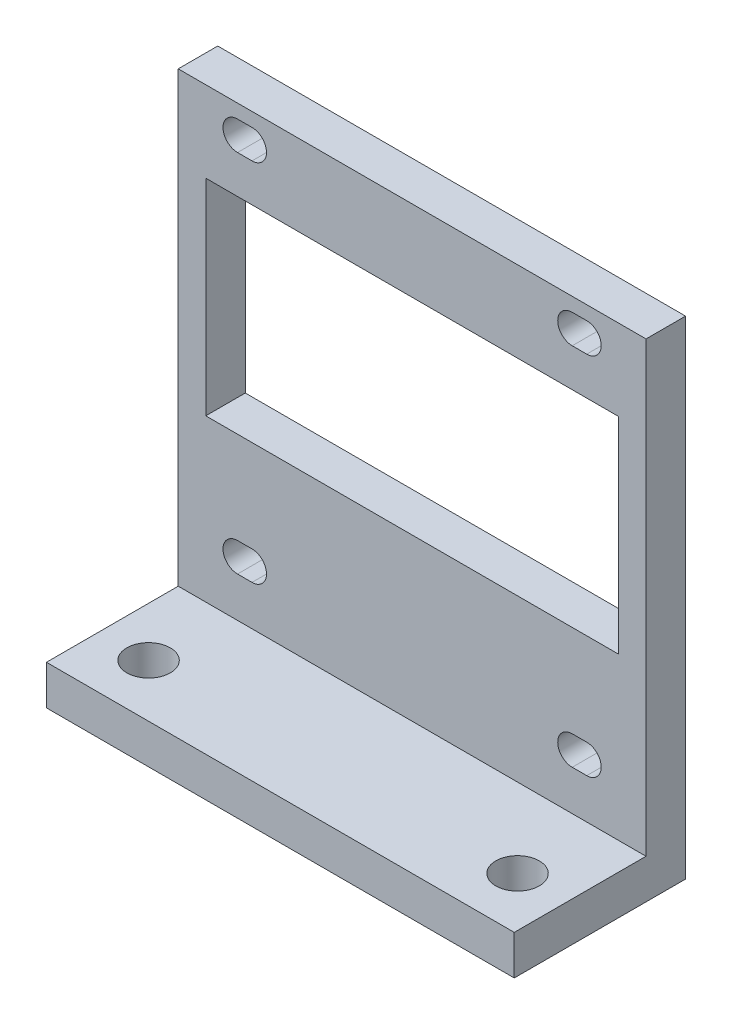
SolidWorks part; units mm, degrees
ref_plane "Front Plane" through (0, 0, 0) normal (0, 0, 1) x (1, 0, 0)
ref_plane "Top Plane" through (0, 0, 0) normal (0, 1, 0) x (1, 0, 0)
ref_plane "Right Plane" through (0, 0, 0) normal (1, 0, 0) x (0, 0, -1)
sketch "Sketch1" plane through (0, 0, 0) normal (0, 0, 1) x (1, 0, 0)
  line L0 (4.5, 34.85) -> (5.6, 34.85) construction
  line L5 (0, 5) -> (35.5, 5) construction
  line L6 (0, 5) -> (0, 37) construction
  line L7 (0, 37) -> (35.5, 37) construction
  line L8 (35.5, 5) -> (35.5, 37) construction
  line L9 (4.5, 35.95) -> (5.6, 35.95)
  line L10 (4.5, 33.75) -> (5.6, 33.75)
  line L11 (29.9, 34.85) -> (31, 34.85) construction
  line L12 (29.9, 35.95) -> (31, 35.95)
  line L13 (29.9, 33.75) -> (31, 33.75)
  line L14 (29.9, 7.15) -> (31, 7.15) construction
  line L15 (29.9, 8.25) -> (31, 8.25)
  line L16 (29.9, 6.05) -> (31, 6.05)
  line L17 (4.5, 7.15) -> (5.6, 7.15) construction
  line L18 (4.5, 8.25) -> (5.6, 8.25)
  line L19 (4.5, 6.05) -> (5.6, 6.05)
  line L21 (0, 0) -> (35.5, 0)
  line L22 (0, 0) -> (0, 37)
  line L23 (0, 37) -> (35.5, 37)
  line L24 (35.5, 0) -> (35.5, 37)
  line L25 (2.09, 15.24) -> (33.41, 15.24)
  line L26 (2.09, 15.24) -> (2.09, 30.86)
  line L27 (2.09, 30.86) -> (33.41, 30.86)
  line L28 (33.41, 15.24) -> (33.41, 30.86)
  arc A0 (4.5, 35.95) -> (4.5, 33.75) centre (4.5, 34.85) ccw
  arc A1 (5.6, 33.75) -> (5.6, 35.95) centre (5.6, 34.85) ccw
  arc A2 (29.9, 35.95) -> (29.9, 33.75) centre (29.9, 34.85) ccw
  arc A3 (31, 33.75) -> (31, 35.95) centre (31, 34.85) ccw
  arc A4 (29.9, 8.25) -> (29.9, 6.05) centre (29.9, 7.15) ccw
  arc A5 (31, 6.05) -> (31, 8.25) centre (31, 7.15) ccw
  arc A6 (4.5, 8.25) -> (4.5, 6.05) centre (4.5, 7.15) ccw
  arc A7 (5.6, 6.05) -> (5.6, 8.25) centre (5.6, 7.15) ccw
  point P7 (5.05, 34.85)
  point P16 (30.45, 34.85)
  point P23 (30.45, 7.15)
  point P30 (5.05, 7.15)
  dimension "D1" = 3.3
  dimension "D2" = 1.1
  dimension "D3" = 5.05
  dimension "D4" = 2.15
  dimension "D5" = 35.5
  dimension "D6" = 32
  dimension "D9" = 5
  dimension "D10" = 15.62
  dimension "D11" = 31.32
  dimension "D12" = 6.14
  dimension "D13" = 2.09
  dimension "D7" = 2
  dimension "D8" = 2
extrude "Boss-Extrude1" add sketch "Sketch1" along normal blind 3
sketch "Sketch2" plane through (0, 0, 0) normal (0, -1, 0) x (1, 0, 0)
  line L0 (35.5, 3) -> (35.5, 0) construction
  line L1 (0, 3) -> (35.5, 3)
  line L2 (0, 3) -> (0, 13)
  line L3 (0, 13) -> (35.5, 13)
  line L4 (35.5, 3) -> (35.5, 13)
  circle A0 centre (3.75, 9) radius 1.65
  circle A1 centre (31.75, 9) radius 1.65
  point P9 (0, 0)
  dimension "D2" = 28
  dimension "D3" = 3.75
  dimension "D4" = 4
  dimension "D5" = 3.3
  dimension "D1" = 10
extrude "Boss-Extrude2" add sketch "Sketch2" against normal blind 3
